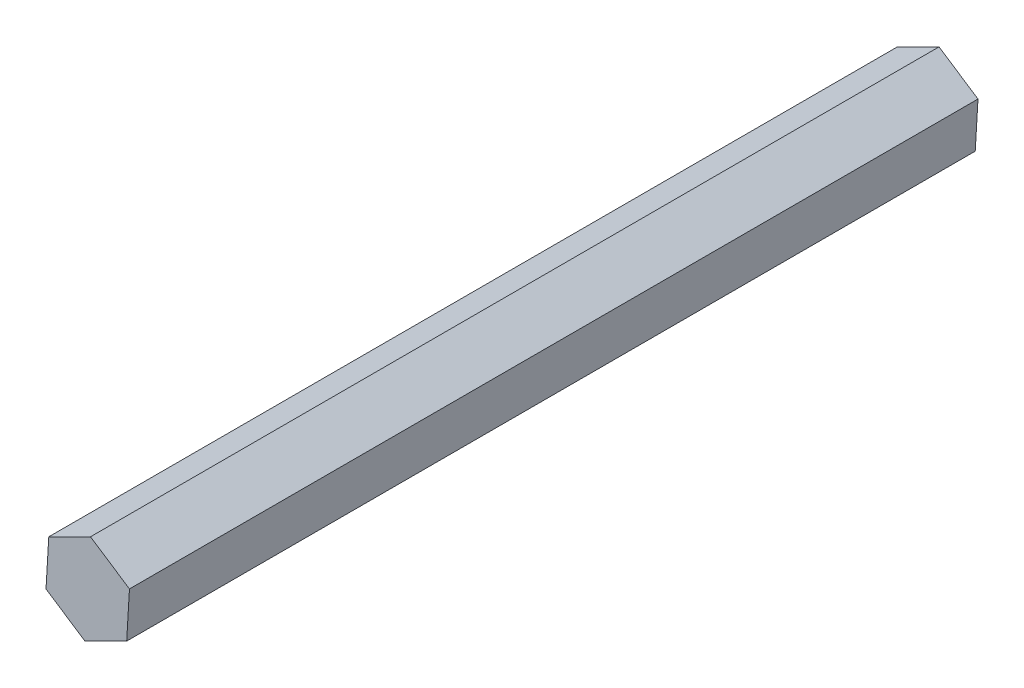
SolidWorks part; units mm, degrees
ref_plane "Front Plane" through (0, 0, 0) normal (0, 0, 1) x (1, 0, 0)
ref_plane "Top Plane" through (0, 0, 0) normal (0, 1, 0) x (1, 0, 0)
ref_plane "Right Plane" through (0, 0, 0) normal (1, 0, 0) x (0, 0, -1)
sketch "Sketch1" plane through (0, 0, 0) normal (0, 0, 1) x (1, 0, 0)
  line L7 (4.9177, 2.4614) -> (0.3272, 5.4895)
  line L8 (0.3272, 5.4895) -> (-4.5905, 3.0281)
  line L9 (-4.5905, 3.0281) -> (-4.9177, -2.4614)
  line L10 (-4.9177, -2.4614) -> (-0.3272, -5.4895)
  line L11 (-0.3272, -5.4895) -> (4.5905, -3.0281)
  line L12 (4.5905, -3.0281) -> (4.9177, 2.4614)
  circle A0 centre (0, 0) radius 4.7625 construction
extrude "Boss-Extrude1" add sketch "Sketch1" along normal blind 100
move or copy body "Body-Move/Copy1" [suppressed] bodies to move or copy 102
